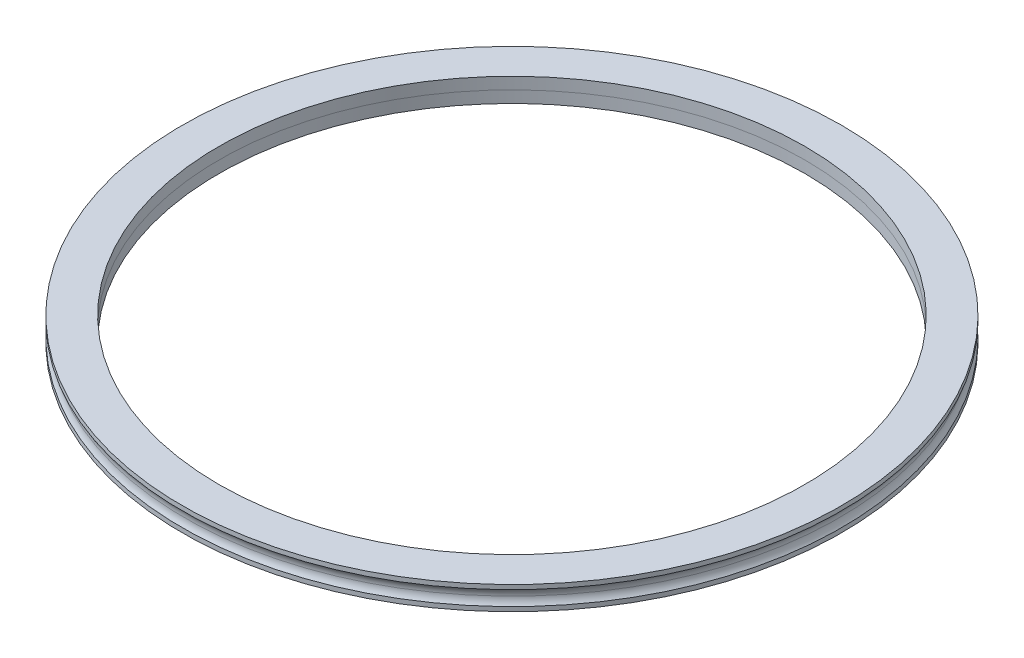
SolidWorks part; units mm, degrees
material "AISI 4340 Steel, normalized"
ref_plane "Front Plane" through (0, 0, 0) normal (0, 0, 1) x (1, 0, 0)
ref_plane "Top Plane" through (0, 0, 0) normal (0, 1, 0) x (1, 0, 0)
ref_plane "Right Plane" through (0, 0, 0) normal (1, 0, 0) x (0, 0, -1)
sketch "Sketch1" plane through (0, 0, 0) normal (0, 0, 1) x (1, 0, 0)
  line L1 (-60, 8.1325) -> (-60, 12.9625) construction
  line L2 (-60, 8.1325) -> (-67.5, 8.1325) construction
  line L3 (-67.5, 8.1325) -> (-67.5, 9.0475) construction
  line L4 (-67.5, 12.0475) -> (-67.5, 12.9625)
  line L5 (-60, 8.1325) -> (-60, 12.9625)
  line L6 (-60, 8.1325) -> (-67.5, 8.1325)
  line L7 (-67.5, 8.1325) -> (-67.5, 9.0475)
  line L8 (-60, 12.9625) -> (-67.5, 12.9625)
  line L10 (0, -200069.0475) -> (0, 200086.9028) construction
  line L11 (0, -200069.0475) -> (0, 200086.9028) construction
  arc A0 (-67.5, 9.0475) -> (-67.5, 12.0475) centre (-69.5, 10.5475) ccw construction
  arc A1 (-67.5, 9.0475) -> (-67.5, 12.0475) centre (-69.5, 10.5475) ccw
revolve "Revolve1" add sketch "Sketch1" angle 360 about L11
ref_plane "Midplane" through (0, 10.5475, 0) normal (0, 1, 0) x (1, 0, 0)
split "Split1" trim tools "Midplane" bodies to split 101 resulting bodies 102 103
